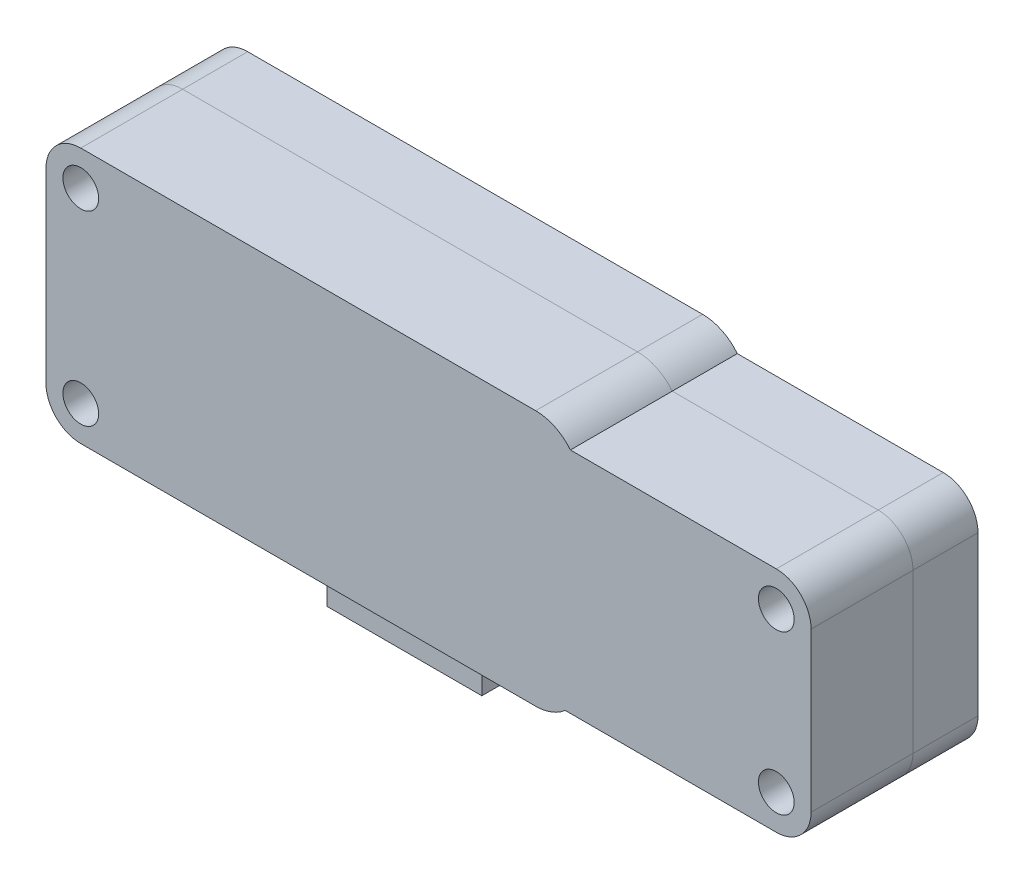
SolidWorks part; units mm, degrees
ref_plane "Front Plane" through (0, 0, 0) normal (0, 0, 1) x (1, 0, 0)
ref_plane "Top Plane" through (0, 0, 0) normal (0, 1, 0) x (1, 0, 0)
ref_plane "Right Plane" through (0, 0, 0) normal (1, 0, 0) x (0, 0, -1)
sketch "Sketch1" plane through (0, 0, 0) normal (0, 0, 1) x (1, 0, 0)
  line L8 (-21.844, 7.62) -> (-21.844, -7.62)
  line L9 (17.78, 11.684) -> (-17.78, 11.684)
  line L10 (21.844, -7.62) -> (21.844, 7.62)
  line L11 (-17.78, -11.684) -> (17.78, -11.684)
  line L12 (-21.844, 7.62) -> (-21.844, -7.62)
  line L13 (17.78, 11.684) -> (-17.78, 11.684)
  line L14 (21.844, -7.62) -> (21.844, 7.62)
  line L15 (-17.78, -11.684) -> (17.78, -11.684)
  arc A8 (-17.78, 11.684) -> (-21.844, 7.62) centre (-17.78, 7.62) ccw
  arc A9 (21.844, 7.62) -> (17.78, 11.684) centre (17.78, 7.62) ccw
  arc A10 (17.78, -11.684) -> (21.844, -7.62) centre (17.78, -7.62) ccw
  arc A11 (-21.844, -7.62) -> (-17.78, -11.684) centre (-17.78, -7.62) ccw
  arc A12 (-17.78, 11.684) -> (-21.844, 7.62) centre (-17.78, 7.62) ccw
  arc A13 (21.844, 7.62) -> (17.78, 11.684) centre (17.78, 7.62) ccw
  arc A14 (17.78, -11.684) -> (21.844, -7.62) centre (17.78, -7.62) ccw
  arc A15 (-21.844, -7.62) -> (-17.78, -11.684) centre (-17.78, -7.62) ccw
  dimension "D1" = 1.524
extrude "Boss-Extrude1" add sketch "Sketch1" against normal blind 12.7 from offset 2.032
ref_plane "Plane2" through (0, 0, -4) normal (0, 0, -1) x (-1, 0, 0)
sketch "Sketch2" plane through (0, 0, -4) normal (0, 0, -1) x (-1, 0, 0)
  line L3 (4.034, -16.0786) -> (4.034, -8.1284)
  line L4 (2.764, -14.8086) -> (-8.836, -14.8086) construction
  line L5 (2.764, -14.8086) -> (2.764, -9.3984) construction
  line L6 (2.764, -9.3984) -> (-8.836, -9.3984) construction
  line L7 (-8.836, -14.8086) -> (-8.836, -9.3984) construction
  line L8 (4.034, -8.1284) -> (-10.106, -8.1284)
  line L9 (-10.106, -16.0786) -> (-10.106, -8.1284)
  line L10 (4.034, -16.0786) -> (-10.106, -16.0786)
  line L12 (2.764, -14.8086) -> (2.764, -9.3984) construction
  line L13 (-8.836, -14.8086) -> (-3.29, -14.8086) construction
  dimension "D1" = 1.27
extrude "Boss-Extrude2" add sketch "Sketch2" along normal offset from surface 1.27 and the other way offset from surface (3.27 mm away) 1.27
sketch "Sketch3" plane through (0, 0, -10.668) normal (0, 0, -1) x (-1, 0, 0)
  line L1 (-3.036, 8.8916) -> (-36.576, 8.8916) construction
  line L2 (-3.036, 8.8916) -> (-3.036, -9.3984) construction
  line L3 (-3.036, -9.3984) -> (-36.576, -9.3984) construction
  line L4 (-36.576, 8.8916) -> (-36.576, -9.3984) construction
  line L5 (-36.576, 8.8916) -> (-36.576, -9.3984) construction
  line L6 (-36.576, -9.3984) -> (-3.036, -9.3984) construction
  line L7 (-1.766, 10.1616) -> (-37.846, 10.1616)
  line L8 (-37.846, 10.1616) -> (-37.846, -10.6684)
  line L9 (-1.766, -10.6684) -> (-37.846, -10.6684)
  line L10 (-1.766, 10.1616) -> (-1.766, -10.6684)
  dimension "D1" = 1.27
extrude "Boss-Extrude3" add sketch "Sketch3" along normal blind 2.54 and the other way up to surface contours L9 L8 L7 L10 other way up to face at (0, 0, 2.032)
sketch "Sketch7" plane through (0, -16.0786, 0) normal (0, -1, 0) x (1, 0, 0)
  line L0 (0.024, -5.762) -> (0.024, -2.238)
  line L1 (0.786, -5) -> (5.286, -5) construction
  line L2 (0.786, -5) -> (0.786, -3) construction
  line L3 (0.786, -3) -> (5.286, -3) construction
  line L4 (5.286, -5) -> (5.286, -3) construction
  line L5 (0.024, -2.238) -> (6.048, -2.238)
  line L6 (6.048, -5.762) -> (6.048, -2.238)
  line L7 (0.024, -5.762) -> (6.048, -5.762)
  dimension "D1" = 0.762
extrude "Cut-Extrude1" cut sketch "Sketch7" against normal blind 2.54
sketch "Sketch11" plane through (0, 0, -10.668) normal (0, 0, -1) x (-1, 0, 0)
  line L4 (17.78, 11.684) -> (23.749, 11.684)
  line L5 (26.924, 7.62) -> (26.924, -7.62)
  line L6 (26.924, 8.509) -> (26.924, -8.509)
  line L7 (17.78, -11.684) -> (23.749, -11.684)
  line L8 (-20.9512, 10.1616) -> (-1.766, 10.1616)
  line L9 (-20.9512, 10.1616) -> (-1.766, 10.1616)
  line L12 (-1.766, 10.1616) -> (-1.766, -10.6684)
  line L13 (-1.766, 10.1616) -> (-1.766, -10.6684)
  line L14 (-1.766, -10.6684) -> (-20.4677, -10.6684)
  line L15 (-1.766, -10.6684) -> (-20.4677, -10.6684)
  line L17 (-17.78, -11.684) -> (17.78, -11.684)
  line L18 (21.844, -7.62) -> (21.844, 7.62)
  line L19 (17.78, 11.684) -> (-17.78, 11.684)
  line L23 (-17.78, -11.684) -> (17.78, -11.684)
  line L25 (17.78, 11.684) -> (-17.78, 11.684)
  arc A2 (23.749, -11.684) -> (26.924, -8.509) centre (23.749, -8.509) ccw
  arc A3 (26.924, 8.509) -> (23.749, 11.684) centre (23.749, 8.509) ccw
  arc A8 (-17.78, 11.684) -> (-20.9512, 10.1616) centre (-17.78, 7.62) ccw
  arc A9 (-20.4677, -10.6684) -> (-17.78, -11.684) centre (-17.78, -7.62) ccw
  arc A10 (17.78, -11.684) -> (21.844, -7.62) centre (17.78, -7.62) ccw
  arc A11 (21.844, 7.62) -> (17.78, 11.684) centre (17.78, 7.62) ccw
  arc A12 (-17.78, 11.684) -> (-20.9512, 10.1616) centre (-17.78, 7.62) ccw
  arc A13 (-20.4677, -10.6684) -> (-17.78, -11.684) centre (-17.78, -7.62) ccw
  dimension "D2" = 3.175
  dimension "D1" = 5.08
  dimension "D3" = 0
extrude "Boss-Extrude5" add sketch "Sketch11" against normal through all
hole_wizard "#4 Clearance Hole4" positions "Sketch13" profile "Sketch12" hole size "#4" standard "ANSI Inch" end condition through all
sketch "Sketch13" plane through (0, 0, -10.668) normal (0, 0, -1) x (-1, 0, 0)
  line L0 (26.924, 0) -> (-37.846, -0.2534) construction
  line L1 (26.924, -8.509) -> (26.924, 8.509) construction
  line L2 (-37.846, 10.1616) -> (-37.846, -10.6684) construction
  point P9 (23.749, 8.509)
  point P12 (23.749, -8.509)
sketch "Sketch12" plane through (-23.749, 8.509, -10.668) normal (1, 0, 0) x (0, 1, 0)
  line L0 (0, 0) -> (0, 12.7)
  line L1 (0, 12.7) -> (1.6319, 12.7)
  line L2 (1.6319, 12.7) -> (1.6319, 0)
  line L5 (1.6319, 0) -> (0, 0)
  line L11 (0, -6.35) -> (0, 107.95) construction
  dimension "Thru Hole Dia." = 3.2639
  dimension "Thru Hole Depth" = 12.7
sketch "Sketch14" plane through (0, 0, -13.208) normal (0, 0, -1) x (-1, 0, 0)
  line L0 (-37.846, 10.1616) -> (-39.751, 10.1616)
  line L1 (-42.926, 6.9866) -> (-42.926, -7.4934)
  line L2 (-39.751, -10.6684) -> (-37.846, -10.6684)
  line L7 (-1.766, -10.6684) -> (-1.766, 10.1616)
  line L8 (-1.766, 10.1616) -> (-37.846, 10.1616)
  line L9 (-37.846, 10.1616) -> (-37.846, -10.6684)
  line L10 (-37.846, -10.6684) -> (-1.766, -10.6684)
  line L13 (-37.846, 10.1616) -> (-37.846, -10.6684)
  arc A0 (-42.926, -7.4934) -> (-39.751, -10.6684) centre (-39.751, -7.4934) ccw
  arc A1 (-42.926, 6.9866) -> (-39.751, 10.1616) centre (-39.751, 6.9866) cw
  point P10 (-42.926, 10.1616)
  dimension "D2" = 3.175
  dimension "D1" = 5.08
  dimension "D3" = 0
extrude "Boss-Extrude6" add sketch "Sketch14" against normal through all
hole_wizard "#4 Clearance Hole5" positions "Sketch16" profile "Sketch15" hole size "#4" standard "ANSI Inch" end condition through all
sketch "Sketch16" plane through (0, 0, -13.208) normal (0, 0, -1) x (-1, 0, 0)
  line L0 (-42.926, -0.2534) -> (-1.766, -0.2534) construction
  line L1 (-42.926, 6.9866) -> (-42.926, -7.4934) construction
  line L2 (-1.766, 10.1616) -> (-1.766, -10.6684) construction
  point P9 (-39.751, 6.9866)
  point P12 (-39.751, -7.4934)
sketch "Sketch15" plane through (39.751, 6.9866, -13.208) normal (1, 0, 0) x (0, 1, 0)
  line L0 (0, 0) -> (0, 15.24)
  line L1 (0, 15.24) -> (1.6319, 15.24)
  line L2 (1.6319, 15.24) -> (1.6319, 0)
  line L5 (1.6319, 0) -> (0, 0)
  line L11 (0, -6.35) -> (0, 107.95) construction
  dimension "Thru Hole Dia." = 3.2639
  dimension "Thru Hole Depth" = 15.24
sketch "Sketch17" plane through (0, 0, -10.668) normal (0, 0, -1) x (-1, 0, 0)
  line L12 (-17.78, -11.684) -> (23.749, -11.684)
  line L13 (26.924, -8.509) -> (26.924, 8.509)
  line L14 (23.749, 11.684) -> (-17.78, 11.684)
  line L15 (-20.9512, 10.1616) -> (-1.766, 10.1616)
  line L16 (-1.766, 10.1616) -> (-1.766, -10.6684)
  line L17 (-1.766, -10.6684) -> (-20.4677, -10.6684)
  line L18 (-17.78, -11.684) -> (23.749, -11.684)
  line L19 (26.924, -8.509) -> (26.924, 8.509)
  line L20 (23.749, 11.684) -> (-17.78, 11.684)
  line L21 (-20.9512, 10.1616) -> (-1.766, 10.1616)
  line L22 (-1.766, 10.1616) -> (-1.766, -10.6684)
  line L23 (-1.766, -10.6684) -> (-20.4677, -10.6684)
  circle A4 centre (23.749, 8.509) radius 1.6319
  circle A5 centre (23.749, -8.509) radius 1.6319
  arc A8 (23.749, -11.684) -> (26.924, -8.509) centre (23.749, -8.509) ccw
  arc A9 (26.924, 8.509) -> (23.749, 11.684) centre (23.749, 8.509) ccw
  arc A10 (-17.78, 11.684) -> (-20.9512, 10.1616) centre (-17.78, 7.62) ccw
  arc A11 (-20.4677, -10.6684) -> (-17.78, -11.684) centre (-17.78, -7.62) ccw
  arc A12 (23.749, -11.684) -> (26.924, -8.509) centre (23.749, -8.509) ccw
  arc A13 (26.924, 8.509) -> (23.749, 11.684) centre (23.749, 8.509) ccw
  arc A14 (-17.78, 11.684) -> (-20.9512, 10.1616) centre (-17.78, 7.62) ccw
  arc A15 (-20.4677, -10.6684) -> (-17.78, -11.684) centre (-17.78, -7.62) ccw
  dimension "D1" = 0
extrude "Boss-Extrude8" add sketch "Sketch17" along normal up to surface (2.54 mm away) up to face at (38.1191, 6.9866, -13.208)
ref_plane "Plane1" through (0, 0, -7.27) normal (0, 0, -1) x (-1, 0, 0)
split "Split1" trim tools "Plane1" bodies to split 109 resulting bodies 107 108
